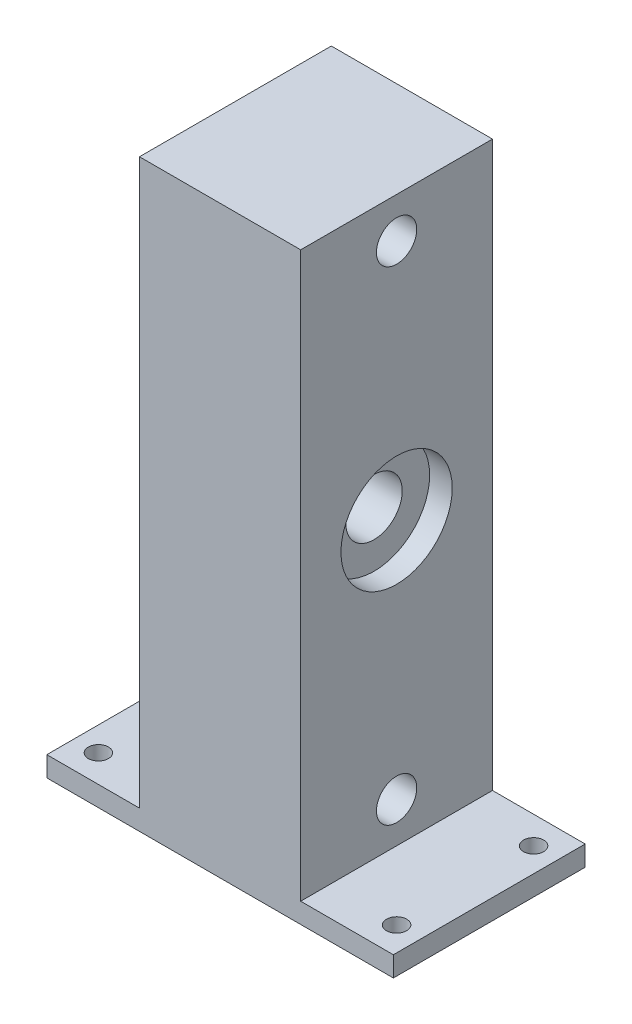
SolidWorks part; units mm, degrees
ref_plane "Front Plane" through (0, 0, 0) normal (0, 0, 1) x (1, 0, 0)
ref_plane "Top Plane" through (0, 0, 0) normal (0, 1, 0) x (1, 0, 0)
ref_plane "Right Plane" through (0, 0, 0) normal (1, 0, 0) x (0, 0, -1)
sketch "Sketch1" plane through (0, 0, 0) normal (0, 0, 1) x (1, 0, 0)
  line L1 (-12.7, 44.45) -> (12.7, 44.45)
  line L2 (-12.7, 44.45) -> (-12.7, -44.45)
  line L3 (-12.7, -44.45) -> (12.7, -44.45)
  line L4 (12.7, 44.45) -> (12.7, -44.45)
  point P5 (0, 44.45)
  point P7 (-12.7, 0)
  dimension "D1" = 25.4
  dimension "D2" = 88.9
extrude "Boss-Extrude1" add sketch "Sketch1" along normal blind 30.226
sketch "Sketch2" plane through (12.7, 0, 0) normal (1, 0, 0) x (0, 0, -1)
  line L0 (0, 0) -> (-95.9488, 0) construction
  line L1 (-30.226, 44.45) -> (0, 44.45) construction
  circle A0 centre (-15.113, 38.1) radius 3.175
  circle A1 centre (-15.113, -38.1) radius 3.175
  point P11 (-15.113, 44.45)
  dimension "D1" = 6.35
  dimension "D2" = 76.2
extrude "Cut-Extrude1" cut sketch "Sketch2" against normal blind 12.7
sketch "Sketch3" plane through (12.7, 0, 0) normal (1, 0, 0) x (0, 0, -1)
  line L0 (-30.226, 44.45) -> (0, 44.45) construction
  circle A0 centre (-15.113, 0) radius 8.763
  point P5 (-15.113, 44.45)
  dimension "D1" = 17.526
extrude "Cut-Extrude2" cut sketch "Sketch3" against normal blind 3.556
sketch "Sketch4" plane through (9.144, 0, 0) normal (1, 0, 0) x (0, 0, -1)
  circle A0 centre (-15.113, 0) radius 10.795
  dimension "D1" = 21.59
extrude "Cut-Extrude3" cut sketch "Sketch4" against normal up to vertex
sketch "Sketch5" plane through (0, -44.45, 0) normal (0, -1, 0) x (1, 0, 0)
  line L0 (-12.7, 0) -> (12.7, 0) construction
  line L1 (-27.305, 30.226) -> (27.305, 30.226)
  line L2 (-27.305, 30.226) -> (-27.305, 0)
  line L3 (-27.305, 0) -> (27.305, 0)
  line L4 (27.305, 30.226) -> (27.305, 0)
  line L5 (-12.7, 30.226) -> (12.7, 30.226) construction
  line L6 (0, 0) -> (0, 41.1105) construction
  dimension "D1" = 54.61
extrude "Boss-Extrude2" add sketch "Sketch5" along normal blind 3.175
sketch "Sketch6" plane through (0, -47.625, 0) normal (0, -1, 0) x (1, 0, 0)
  line L0 (-27.305, 15.113) -> (27.305, 15.113) construction
  line L1 (-27.305, 30.226) -> (-27.305, 0) construction
  line L2 (27.305, 0) -> (27.305, 30.226) construction
  circle A0 centre (-23.495, 25.908) radius 1.5875
  circle A1 centre (-23.495, 4.318) radius 1.5875
  circle A2 centre (23.495, 4.318) radius 1.5875
  circle A3 centre (23.495, 25.908) radius 1.5875
  dimension "D1" = 3.175
  dimension "D2" = 21.59
  dimension "D3" = 21.59
  dimension "D4" = 3.81
  dimension "D5" = 3.81
extrude "Cut-Extrude4" cut sketch "Sketch6" against normal up to vertex (3.175 mm away)
sketch "Sketch8" plane through (9.144, 0, 0) normal (-1, 0, 0) x (0, 0, 1)
  circle A0 centre (15.113, 0) radius 6.35
  circle A1 centre (15.113, 0) radius 10.795 construction
  circle A2 centre (15.113, 0) radius 10.795
  dimension "D1" = 12.7
extrude "Boss-Extrude3" add sketch "Sketch8" along normal blind 2.54
sketch "Sketch9" plane through (6.604, 0, 0) normal (-1, 0, 0) x (0, 0, 1)
  circle A1 centre (15.113, 0) radius 10.795
  circle A2 centre (15.113, 0) radius 10.795
  dimension "D1" = 0
extrude "Boss-Extrude4" add sketch "Sketch9" along normal up to surface (19.304 mm away) up to face at (-12.7, 0, 4.318)
sketch "Sketch10" plane through (9.144, 0, 0) normal (1, 0, 0) x (0, 0, -1)
  circle A1 centre (-15.113, 0) radius 8.763
  circle A2 centre (-15.113, 0) radius 8.763
  dimension "D1" = 0
extrude "Boss-Extrude5" add sketch "Sketch10" against normal blind 10.16
sketch "Sketch12" plane through (12.7, 0, 0) normal (1, 0, 0) x (0, 0, -1)
  circle A0 centre (-15.113, 0) radius 4.445
  circle A1 centre (-15.113, 0) radius 8.763
  circle A2 centre (-15.113, 0) radius 8.763
  dimension "D2" = 8.89
  dimension "D1" = 0
extrude "Cut-Extrude5" cut sketch "Sketch12" against normal blind 12.7 contours A0
